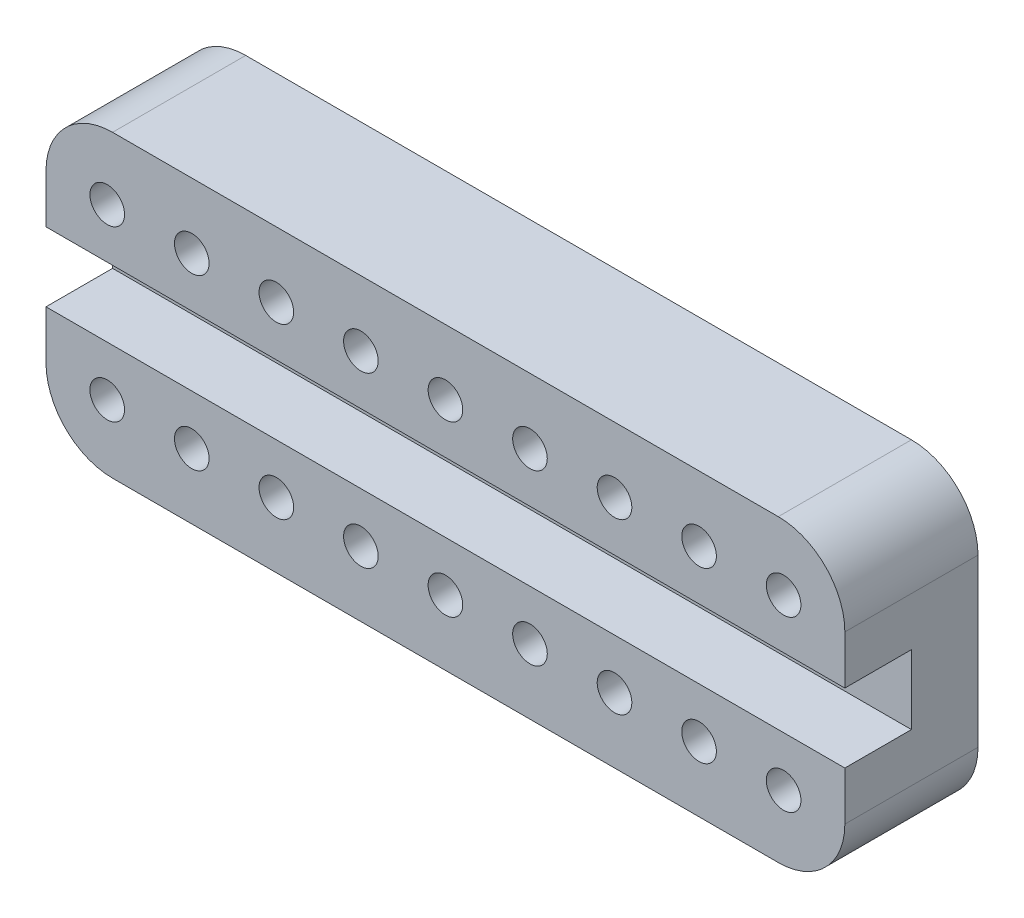
SolidWorks part; units mm, degrees
ref_plane "前视基准面" through (0, 0, 0) normal (0, 0, 1) x (1, 0, 0)
ref_plane "上视基准面" through (0, 0, 0) normal (0, 1, 0) x (1, 0, 0)
ref_plane "右视基准面" through (0, 0, 0) normal (1, 0, 0) x (0, 0, -1)
sketch "草图1" plane through (0, 0, 0) normal (0, 0, 1) x (1, 0, 0)
  line L0 (-60, 0) -> (60, 0) construction
  line L1 (-60, 22.5) -> (60, 22.5)
  line L2 (-60, 22.5) -> (-60, -22.5)
  line L3 (-60, -22.5) -> (60, -22.5)
  line L4 (60, 22.5) -> (60, -22.5)
  line L5 (-60, 22.5) -> (60, -22.5) construction
  line L6 (-60, -22.5) -> (60, 22.5) construction
  circle A0 centre (-50.8, 12.7) radius 2.6
  circle A1 centre (-50.8, 0) radius 2.6
  circle A2 centre (-50.8, -12.7) radius 2.6
  circle A3 centre (-38.1, 12.7) radius 2.6
  circle A4 centre (-38.1, 0) radius 2.6
  circle A5 centre (-38.1, -12.7) radius 2.6
  circle A6 centre (-25.4, 12.7) radius 2.6
  circle A7 centre (-25.4, 0) radius 2.6
  circle A8 centre (-25.4, -12.7) radius 2.6
  circle A9 centre (-12.7, 12.7) radius 2.6
  circle A10 centre (-12.7, 0) radius 2.6
  circle A11 centre (-12.7, -12.7) radius 2.6
  circle A12 centre (0, 12.7) radius 2.6
  circle A13 centre (0, 0) radius 2.6
  circle A14 centre (0, -12.7) radius 2.6
  circle A15 centre (12.7, 12.7) radius 2.6
  circle A16 centre (12.7, 0) radius 2.6
  circle A17 centre (12.7, -12.7) radius 2.6
  circle A18 centre (25.4, 12.7) radius 2.6
  circle A19 centre (25.4, 0) radius 2.6
  circle A20 centre (25.4, -12.7) radius 2.6
  circle A21 centre (38.1, 12.7) radius 2.6
  circle A22 centre (38.1, 0) radius 2.6
  circle A23 centre (38.1, -12.7) radius 2.6
  circle A24 centre (50.8, 12.7) radius 2.6
  circle A25 centre (50.8, 0) radius 2.6
  circle A26 centre (50.8, -12.7) radius 2.6
  point P0 (0, 0)
  dimension "D5" = 5.2
  dimension "D8" = 12.7
  dimension "D1" = 45
  dimension "D2" = 120
  dimension "D3" = 9.2
  dimension "D6" = 12.7
  dimension "D4" = 3
  dimension "D7" = 9
extrude "凸台-拉伸1" add sketch "草图1" along normal blind 20
fillet "圆角1" radius 10 4 edges at (60, 22.5, 10) (60, -22.5, 10) (-60, -22.5, 10) (-60, 22.5, 10)
sketch "草图2" plane through (0, 0, 20) normal (0, 0, 1) x (1, 0, 0)
  line L0 (-60, 0) -> (65.8812, 0) construction
  line L1 (-60, 5.2) -> (65.8812, 5.2)
  line L2 (-60, -5.2) -> (65.8812, -5.2)
  line L3 (-60, 12.5) -> (-60, -12.5) construction
  arc A2 (-60, 5.2) -> (-60, -5.2) centre (-60, 0) ccw
  arc A3 (65.8812, -5.2) -> (65.8812, 5.2) centre (65.8812, 0) ccw
  point P1 (-38.1, 0)
  point P4 (-60, 0)
  point P6 (2.9406, 0)
  point P13 (38.1, 0)
  point P14 (65.8812, 0)
  dimension "D1" = 5.2
extrude "切除-拉伸1" cut sketch "草图2" against normal blind 10
